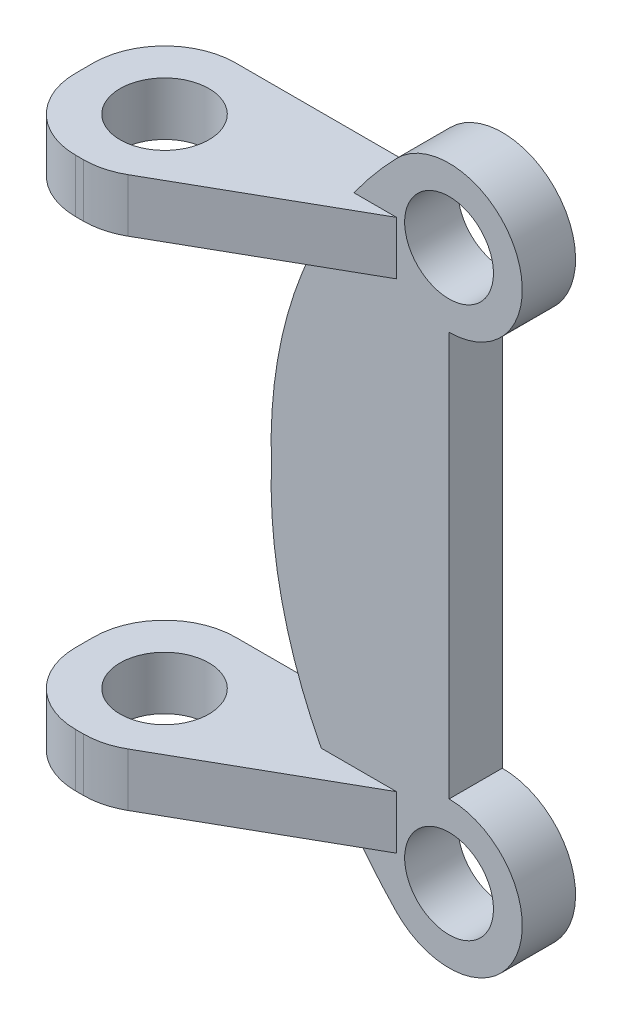
SolidWorks part; units mm, degrees
ref_plane "Alzado" through (0, 0, 0) normal (0, 0, 1) x (1, 0, 0)
ref_plane "Planta" through (0, 0, 0) normal (0, 1, 0) x (1, 0, 0)
ref_plane "Vista lateral" through (0, 0, 0) normal (1, 0, 0) x (0, 0, -1)
sketch "Croquis1" plane through (0, 0, 0) normal (0, 0, 1) x (1, 0, 0)
  line L0 (2.6975, -20.2821) -> (6.4916, -20.2821)
  line L1 (6.4916, 19.1078) -> (2.6975, 19.1078)
  circle A0 centre (3.493, 14.9129) radius 1.5
  circle A1 centre (3.493, -16.0871) radius 1.5
  arc A2 (1.3255, -19.7374) -> (2.6975, -20.2821) centre (2.6975, -18.2821) ccw
  arc A3 (-6.507, -0.5871) -> (1.3255, -19.7374) centre (18.4745, -1.5464) ccw
  arc A4 (1.3255, 18.5631) -> (-6.507, -0.5871) centre (18.4745, 0.3721) ccw
  arc A5 (2.6975, 19.1078) -> (1.3255, 18.5631) centre (2.6975, 17.1078) ccw
sketch "Croquis2" plane through (0, 0, 0) normal (0, 0, 1) x (1, 0, 0)
  line L0 (-6.507, -0.5871) -> (0, -0.5871) construction
  line L1 (3.493, 10.7906) -> (3.493, -11.9649)
  circle A0 centre (3.493, 14.9129) radius 2.5
  circle A1 centre (3.493, -16.0871) radius 2.5
  arc A2 (0.5349, -18.9582) -> (3.493, -11.9649) centre (3.493, -16.0871) ccw
  arc A3 (0.5349, -18.9582) -> (-6.507, -0.5871) centre (18.4745, -1.5464) cw
  arc A4 (-6.507, -0.5871) -> (1.3255, -19.7374) centre (18.4745, -1.5464) ccw construction
  arc A5 (0.5349, 17.7839) -> (-6.507, -0.5871) centre (18.4745, 0.3721) ccw
  arc A6 (0.5349, 17.7839) -> (3.493, 10.7906) centre (3.493, 14.9129) cw
  circle A7 centre (3.493, 14.9129) radius 2.5
extrude "Saliente-Extruir1" add sketch "Croquis2" along normal blind 3
ref_plane "Plano1" through (0, -0.5871, 0) normal (0, 1, 0) x (1, 0, 0)
sketch "Croquis4" plane through (0, -0.5871, 0) normal (0, 1, 0) x (1, 0, 0)
  line L0 (0.5349, -3) -> (-9.1065, -8.4779)
  line L1 (-11.0824, -9) -> (-11.5255, -9)
  line L2 (-15.5255, -5) -> (-15.5255, -4)
  line L3 (-11.5255, 0) -> (0.5349, 0)
  line L6 (-13.5255, -4.5) -> (-15.5255, -4.5) construction
  line L7 (0.5349, 0) -> (-6.5255, 0) construction
  line L9 (-6.5255, 0) -> (-6.5255, -3) construction
  line L10 (0.5349, -3) -> (0.5349, 0)
  circle A0 centre (-11.0255, -4.5) radius 2.5
  arc A1 (-15.5255, -4) -> (-11.5255, 0) centre (-11.5255, -4) cw
  arc A2 (-11.5255, -9) -> (-15.5255, -5) centre (-11.5255, -5) cw
  arc A3 (-9.1065, -8.4779) -> (-11.0824, -9) centre (-11.0824, -5) cw
  point P2 (0, 0)
  point P4 (-9.2368, -9)
  point P8 (-10.0255, -9)
  point P15 (-15.5255, 0)
  point P18 (-15.5255, -9)
  dimension "D3" = 5
  dimension "D5" = 4
  dimension "D7" = 4
  dimension "D1" = 9
  dimension "D2" = 4.5
  dimension "D4" = 2
  dimension "D6" = 1.5
extrude "Saliente-Extruir2" add sketch "Croquis4" along normal blind 3 from offset 12.5
mirror "Simetría1" about plane through (0, -0.5871, 0) normal (0, 1, 0) of "Saliente-Extruir2"
